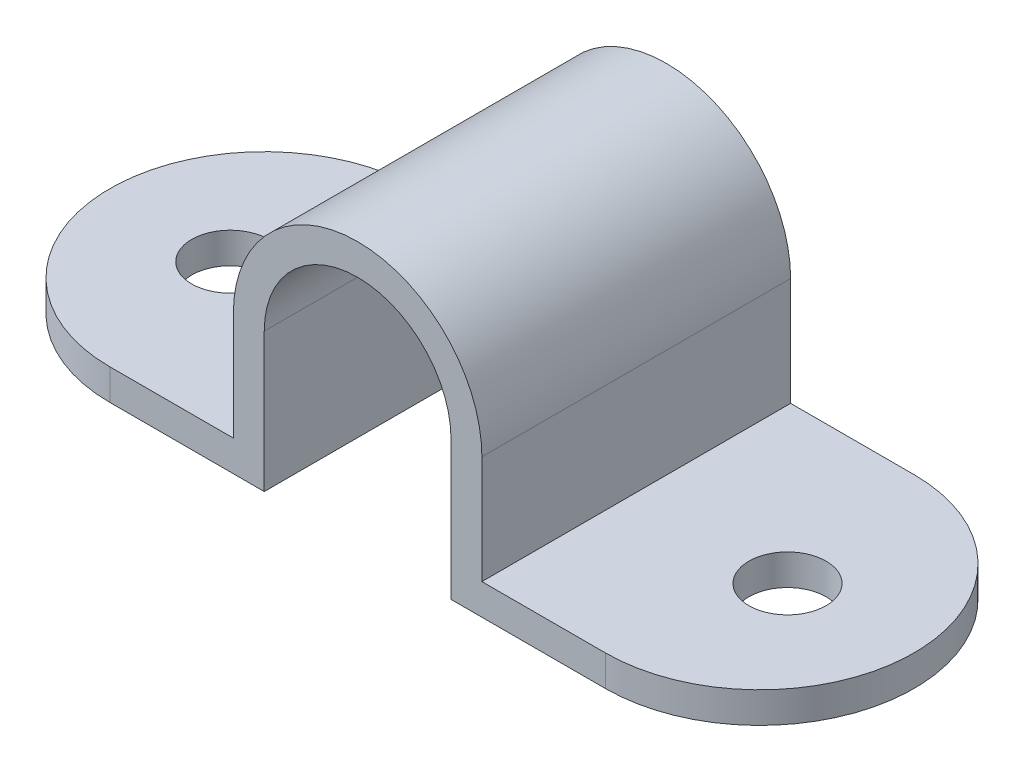
SolidWorks part; units mm, degrees
material "1060 Alaşım"
ref_plane "Ön Düzlem" through (0, 0, 0) normal (0, 0, 1) x (1, 0, 0)
ref_plane "Üst Düzlem" through (0, 0, 0) normal (0, 1, 0) x (1, 0, 0)
ref_plane "Sağ Düzlem" through (0, 0, 0) normal (1, 0, 0) x (0, 0, -1)
sketch "Çizim1" plane through (0, 0, 0) normal (0, 0, 1) x (1, 0, 0)
  line L2 (-6.05, 0) -> (6.05, 0) construction
  line L7 (-6.05, 0) -> (-6.05, -9)
  line L8 (6.05, 0) -> (6.05, -9)
  line L9 (-6.05, -9) -> (-16.05, -9)
  line L10 (6.05, -9) -> (16.05, -9)
  line L11 (8.05, -7) -> (16.05, -7)
  line L12 (8.05, 0) -> (8.05, -7)
  line L13 (-8.05, 0) -> (-8.05, -7)
  line L14 (-8.05, -7) -> (-16.05, -7)
  line L15 (16.05, -9) -> (16.05, -7)
  line L16 (-16.05, -9) -> (-16.05, -7)
  arc A0 (6.05, 0) -> (-6.05, 0) centre (0, 0) ccw
  arc A2 (8.05, 0) -> (-8.05, 0) centre (0, 0) ccw
  dimension "D1" = 12.1
  dimension "D2" = 9
  dimension "D3" = 10
  dimension "D4" = 2
extrude "Yükseklik-Ekstrüzyon1" add sketch "Çizim1" along normal blind 20
sketch "Çizim2" plane through (0, -7, 0) normal (0, 1, 0) x (1, 0, 0)
  line L1 (16.05, 0) -> (16.05, -20)
  line L2 (16.05, -20) -> (16.05, 0) construction
  arc A1 (16.05, 0) -> (16.05, -20) centre (16.05, -10) cw
  point P8 (16.05, -10)
  dimension "D1" = 10
extrude "Yükseklik-Ekstrüzyon2" add sketch "Çizim2" against normal blind 2
mirror "Aynalama1" about plane through (0, 0, 0) normal (1, 0, 0) of "Yükseklik-Ekstrüzyon2"
sketch "Çizim3" plane through (0, -7, 0) normal (0, 1, 0) x (1, 0, 0)
  line L2 (-8.05, -20) -> (-8.05, 0) construction
  line L3 (8.05, -20) -> (8.05, 0) construction
  circle A0 centre (18.05, -10.202) radius 2.5
  circle A1 centre (-18.05, -10.202) radius 2.5
  dimension "D1" = 5
  dimension "D2" = 10
  dimension "D3" = 10
  dimension "D4" = 10
  dimension "D5" = 10
extrude "Kes-Ekstrüzyon1" cut sketch "Çizim3" against normal blind 10
